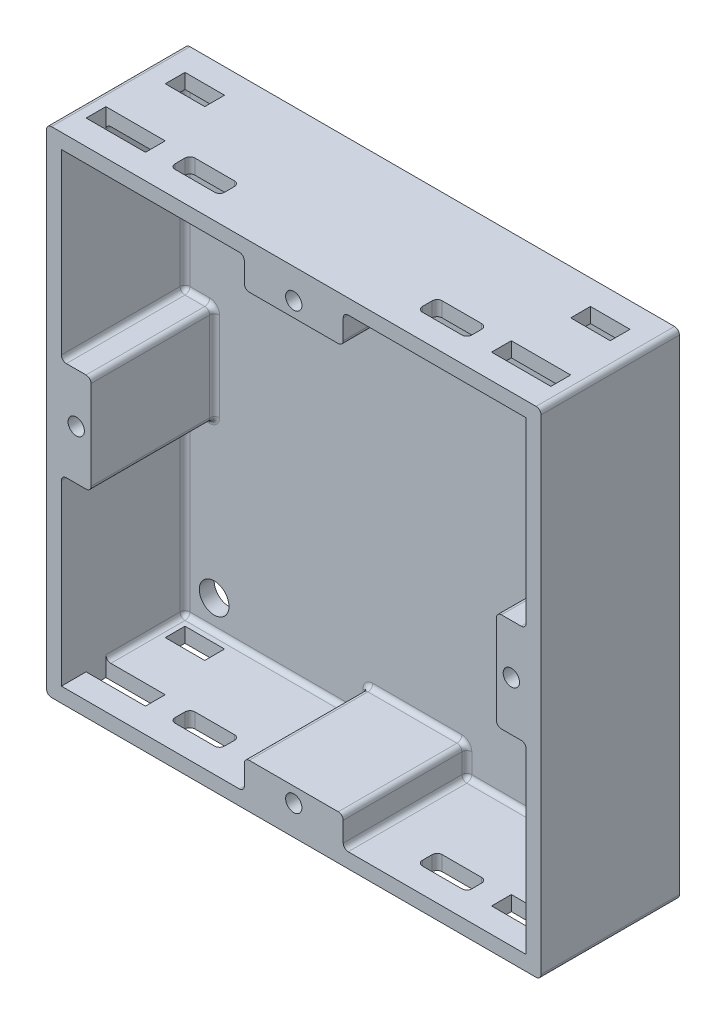
SolidWorks part; units mm, degrees
ref_plane "Front Plane" through (0, 0, 0) normal (0, 0, 1) x (1, 0, 0)
ref_plane "Top Plane" through (0, 0, 0) normal (0, 1, 0) x (1, 0, 0)
ref_plane "Right Plane" through (0, 0, 0) normal (1, 0, 0) x (0, 0, -1)
sketch "Sketch1" plane through (0, 0, 0) normal (0, 0, 1) x (1, 0, 0)
  line L1 (0, 0) -> (100, 0)
  line L2 (0, 0) -> (0, 100)
  line L3 (0, 100) -> (100, 100)
  line L4 (100, 0) -> (100, 100)
  dimension "D1" = 100
  dimension "D2" = 100
extrude "Boss-Extrude1" add sketch "Sketch1" along normal blind 3
sketch "Sketch2" plane through (0, 0, 3) normal (0, 0, 1) x (1, 0, 0)
  line L1 (0, 100) -> (100, 100)
  line L2 (0, 100) -> (0, 0)
  line L3 (0, 0) -> (100, 0)
  line L4 (100, 100) -> (100, 0)
  line L5 (3, 97) -> (97, 97)
  line L6 (3, 97) -> (3, 3)
  line L7 (3, 3) -> (97, 3)
  line L8 (97, 97) -> (97, 3)
  dimension "D1" = 3
  dimension "D2" = 3
  dimension "D3" = 3
extrude "Boss-Extrude2" add sketch "Sketch2" along normal blind 25
sketch "Sketch5" plane through (0, 0, 32.5) normal (0, 0, 1) x (1, 0, 0)
  line L0 (3, 3) -> (97, 3) construction
  line L1 (3, 97) -> (3, 3) construction
  line L2 (97, 3) -> (97, 97) construction
  line L5 (97, 97) -> (3, 97) construction
  circle A0 centre (8.9, 8.9) radius 3
  circle A1 centre (8.9, 91.1) radius 3
  circle A2 centre (91.1, 91.1) radius 3
  circle A3 centre (91.1, 8.9) radius 3
  dimension "D1" = 6
  dimension "D2" = 5.9
  dimension "D3" = 5.9
  dimension "D4" = 5.9
  dimension "D5" = 5.9
extrude "Cut-Extrude1" cut sketch "Sketch5" against normal through all
sketch "Sketch6" plane through (0, 0, 0) normal (0, -1, 0) x (1, 0, 0)
  line L0 (0, 28) -> (100, 28) construction
  line L1 (3, 19) -> (15, 19)
  line L2 (3, 19) -> (3, 23)
  line L3 (3, 23) -> (15, 23)
  line L4 (15, 19) -> (15, 23)
  line L5 (97, 28) -> (97, 3) construction
  line L7 (97, 23) -> (85, 23)
  line L8 (97, 23) -> (97, 19)
  line L9 (97, 19) -> (85, 19)
  line L10 (85, 23) -> (85, 19)
  line L11 (3, 3) -> (97, 3) construction
  line L12 (0, 28) -> (0, 0) construction
  line L13 (100, 28) -> (100, 0) construction
  line L14 (13, 9) -> (5, 9)
  line L15 (13, 9) -> (13, 5)
  line L16 (13, 5) -> (5, 5)
  line L17 (5, 9) -> (5, 5)
  line L18 (3, 28) -> (3, 3) construction
  line L20 (87, 9) -> (95, 9)
  line L21 (87, 9) -> (87, 5)
  line L22 (87, 5) -> (95, 5)
  line L23 (95, 9) -> (95, 5)
  dimension "D1" = 5
  dimension "D2" = 4
  dimension "D3" = 12
  dimension "D4" = 3
  dimension "D5" = 3
  dimension "D6" = 8
  dimension "D7" = 4
  dimension "D8" = 2
  dimension "D9" = 2
  dimension "D10" = 8
  dimension "D11" = 4
  dimension "D12" = 2
extrude "Cut-Extrude3" cut sketch "Sketch6" against normal through all
sketch "Sketch7" plane through (0, 0, 3) normal (0, 0, 1) x (1, 0, 0)
  line L0 (3, 97) -> (3, 3) construction
  line L1 (3, 60) -> (9, 60)
  line L2 (3, 60) -> (3, 40)
  line L3 (3, 40) -> (9, 40)
  line L4 (9, 60) -> (9, 40)
  line L5 (97, 97) -> (3, 97) construction
  line L6 (40, 97) -> (60, 97)
  line L7 (40, 97) -> (40, 91)
  line L8 (40, 91) -> (60, 91)
  line L9 (60, 97) -> (60, 91)
  line L10 (97, 3) -> (97, 97) construction
  line L11 (97, 60) -> (91, 60)
  line L12 (97, 60) -> (97, 40)
  line L13 (97, 40) -> (91, 40)
  line L14 (91, 60) -> (91, 40)
  line L15 (3, 3) -> (97, 3) construction
  line L16 (60, 3) -> (40, 3)
  line L17 (60, 3) -> (60, 9)
  line L18 (60, 9) -> (40, 9)
  line L19 (40, 3) -> (40, 9)
  line L20 (15.4, 100) -> (0, 100) construction
  line L22 (0, 100) -> (0, 77.4) construction
  dimension "D1" = 6
  dimension "D2" = 20
  dimension "D3" = 40
  dimension "D4" = 40
extrude "Boss-Extrude4" add sketch "Sketch7" along normal up to surface (25 mm away) up to face at (50, 50, 28)
hole_wizard "M4x0.7 Tapped Hole1" positions "Sketch8" profile "Sketch10" tap size "M4x0.7" standard "ANSI Metric"
sketch "Sketch8" plane through (0, 0, 28) normal (0, 0, 1) x (1, 0, 0)
  line L0 (9, 40) -> (9, 60) construction
  line L1 (3, 40) -> (9, 40) construction
  line L3 (40, 91) -> (60, 91) construction
  line L4 (60, 9) -> (40, 9) construction
  line L5 (60, 91) -> (60, 97) construction
  line L6 (91, 60) -> (91, 40) construction
  point P0 (6, 50)
  point P2 (50, 94)
  point P4 (94, 50)
  point P6 (50, 6)
  dimension "D1" = 3
  dimension "D2" = 10
  dimension "D3" = 3
  dimension "D4" = 3
  dimension "D5" = 10
  dimension "D6" = 3
sketch "Sketch10" plane through (6, 50, 28) normal (1, 0, 0) x (0, -1, 0)
  line L0 (0, 0) -> (0, 20.9914)
  line L1 (0, 20.9914) -> (1.65, 20)
  line L2 (1.65, 20) -> (1.65, 0)
  line L5 (1.65, 0) -> (0, 0)
  line L10 (0, 20.9914) -> (-1.65, 20) construction
  line L11 (0, -6.35) -> (0, 107.95) construction
  dimension "Tap Drill Dia." = 3.3
  dimension "Tap Drill Depth" = 20
  dimension "Drill Angle" = 118
cosmetic thread "Hole Thread5" parameters "D1"=8, "D2"=4
cosmetic thread "Hole Thread6" parameters "D1"=8, "D2"=4
cosmetic thread "Hole Thread7" parameters "D1"=8, "D2"=4
cosmetic thread "Hole Thread8" parameters "D1"=8, "D2"=4
fillet "Fillet1" radius 1 1 edges at (0, 0, 14)
fillet "Fillet2" radius 1 1 edges at (100, 0, 14)
fillet "Fillet3" radius 1 1 edges at (0, 100, 14)
fillet "Fillet4" radius 1 1 edges at (100, 100, 14)
fillet "Fillet5" radius 1 1 edges at (40, 3, 15.5)
fillet "Fillet6" radius 1 1 edges at (60, 3, 15.5)
fillet "Fillet7" radius 1 1 edges at (97, 40, 15.5)
fillet "Fillet8" radius 1 1 edges at (97, 60, 15.5)
fillet "Fillet9" radius 1 1 edges at (3, 60, 15.5)
fillet "Fillet10" radius 1 1 edges at (3, 40, 15.5)
fillet "Fillet11" radius 1 1 edges at (40, 97, 15.5)
fillet "Fillet12" radius 1 1 edges at (60, 97, 15.5)
fillet "Fillet22" radius 1 1 edges at (60, 9, 15.5)
fillet "Fillet23" radius 1 1 edges at (40, 9, 15.5)
fillet "Fillet24" radius 1 1 edges at (91, 60, 15.5)
fillet "Fillet25" radius 1 1 edges at (91, 40, 15.5)
fillet "Fillet26" radius 1 1 edges at (9, 60, 15.5)
fillet "Fillet27" radius 1 1 edges at (9, 40, 15.5)
fillet "Fillet28" radius 1 1 edges at (60, 91, 15.5)
fillet "Fillet29" radius 1 1 edges at (40, 91, 15.5)
fillet "Fillet30" radius 1 9 edges at (79, 3, 3) (60.2929, 3.2929, 3) (21, 3, 3) (39.7071, 3.2929, 3) (40, 6, 3) (40.2929, 8.7071, 3) (50, 9, 3) (59.7071, 8.7071, 3) (60, 6, 3)
fillet "Fillet31" radius 1 11 edges at (3, 3, 11.5) (3, 3.2929, 3.2929) (3, 21.5, 3) (3.2929, 39.7071, 3) (6, 40, 3) (8.7071, 40.2929, 3) (9, 50, 3) (8.7071, 59.7071, 3) (3, 79, 3) (3.2929, 60.2929, 3) (6, 60, 3)
fillet "Fillet32" radius 1 11 edges at (3, 97, 11.5) (3.2929, 97, 3.2929) (21.5, 97, 3) (39.7071, 96.7071, 3) (40, 94, 3) (40.2929, 91.2929, 3) (79, 97, 3) (60.2929, 96.7071, 3) (60, 94, 3) (59.7071, 91.2929, 3) (50, 91, 3)
fillet "Fillet33" radius 1 13 edges at (97, 97, 11.5) (97, 96.7071, 3.2929) (97, 78.5, 3) (96.7071, 60.2929, 3) (97, 3, 11.5) (97, 3.2929, 3.2929) (97, 21.5, 3) (96.7071, 39.7071, 3) (94, 40, 3) (91.2929, 40.2929, 3) (91, 50, 3) (91.2929, 59.7071, 3) (94, 60, 3)
sketch "Sketch12" plane through (0, 0, 0) normal (0, -1, 0) x (1, 0, 0)
  line L0 (15, 19) -> (4, 19) construction
  line L1 (21, 19) -> (29, 19)
  line L2 (20, 20) -> (20, 22)
  line L3 (21, 23) -> (29, 23)
  line L4 (30, 20) -> (30, 22)
  line L5 (71, 19) -> (79, 19)
  line L6 (70, 20) -> (70, 22)
  line L7 (71, 23) -> (79, 23)
  line L8 (80, 20) -> (80, 22)
  line L11 (15, 19) -> (15, 23) construction
  line L12 (85, 23) -> (85, 19) construction
  line L13 (15, 23) -> (3, 23) construction
  arc A0 (20, 22) -> (21, 23) centre (21, 22) cw
  arc A1 (30, 22) -> (29, 23) centre (29, 22) ccw
  arc A2 (29, 19) -> (30, 20) centre (29, 20) ccw
  arc A3 (21, 19) -> (20, 20) centre (21, 20) cw
  arc A4 (71, 19) -> (70, 20) centre (71, 20) cw
  arc A5 (79, 19) -> (80, 20) centre (79, 20) ccw
  arc A6 (79, 23) -> (80, 22) centre (79, 22) cw
  arc A7 (70, 22) -> (71, 23) centre (71, 22) cw
  point P12 (15, 21)
  point P17 (20, 23)
  point P20 (30, 23)
  point P23 (30, 19)
  dimension "D3" = 1
  dimension "D6" = 1
  dimension "D7" = 1
  dimension "D8" = 1
  dimension "D9" = 1
  dimension "D1" = 10
  dimension "D2" = 4
  dimension "D4" = 5
  dimension "D5" = 5
extrude "Cut-Extrude5" cut sketch "Sketch12" against normal through all
